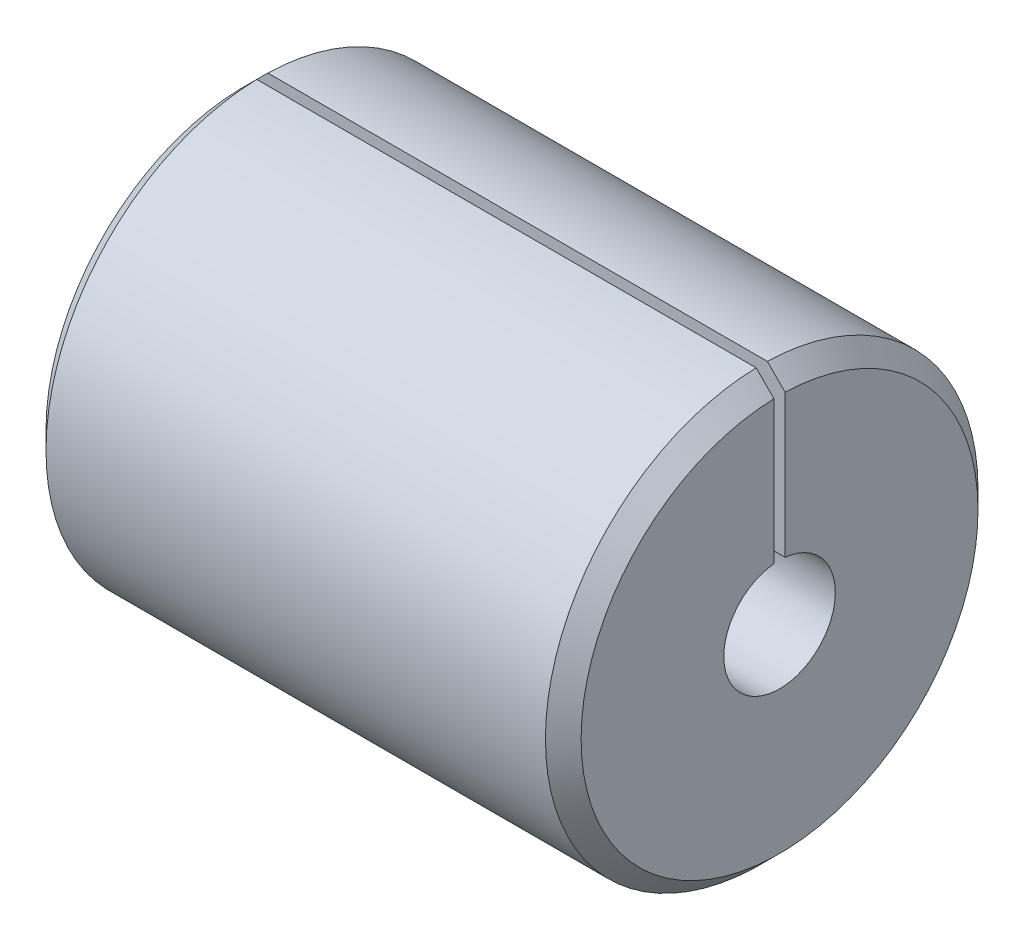
SolidWorks part; units mm, degrees
ref_plane "Front Plane" through (0, 0, 0) normal (0, 0, 1) x (1, 0, 0)
ref_plane "Top Plane" through (0, 0, 0) normal (0, 1, 0) x (1, 0, 0)
ref_plane "Right Plane" through (0, 0, 0) normal (1, 0, 0) x (0, 0, -1)
sketch "Sketch1" plane through (0, 0, 0) normal (1, 0, 0) x (0, 0, -1)
  circle A0 centre (0, 0) radius 9.7
  dimension "D1" = 19.4
extrude "Boss-Extrude1" add sketch "Sketch1" along normal blind 24
sketch "Sketch2" plane through (24, 0, 0) normal (1, 0, 0) x (0, 0, -1)
  circle A0 centre (0, 0) radius 2.5
  dimension "D1" = 5
extrude "Cut-Extrude1" cut sketch "Sketch2" against normal through all
sketch "Sketch3" plane through (0, 0, 0) normal (-1, 0, 0) x (0, 0, 1)
  line L1 (-0.25, 19.4) -> (0.25, 19.4)
  line L2 (-0.25, 19.4) -> (-0.25, 0)
  line L3 (-0.25, 0) -> (0.25, 0)
  line L4 (0.25, 19.4) -> (0.25, 0)
  line L5 (-0.25, 19.4) -> (0.25, 0) construction
  line L6 (-0.25, 0) -> (0.25, 19.4) construction
  circle A0 centre (0, 0) radius 9.7 construction
  point P0 (0, 9.7)
  dimension "D1" = 0.5
extrude "Cut-Extrude2" cut sketch "Sketch3" against normal through all
chamfer "Chamfer1" distance 0.8 angle 45 2 edges at (0, -9.7, 0) (24, -9.7, 0)
